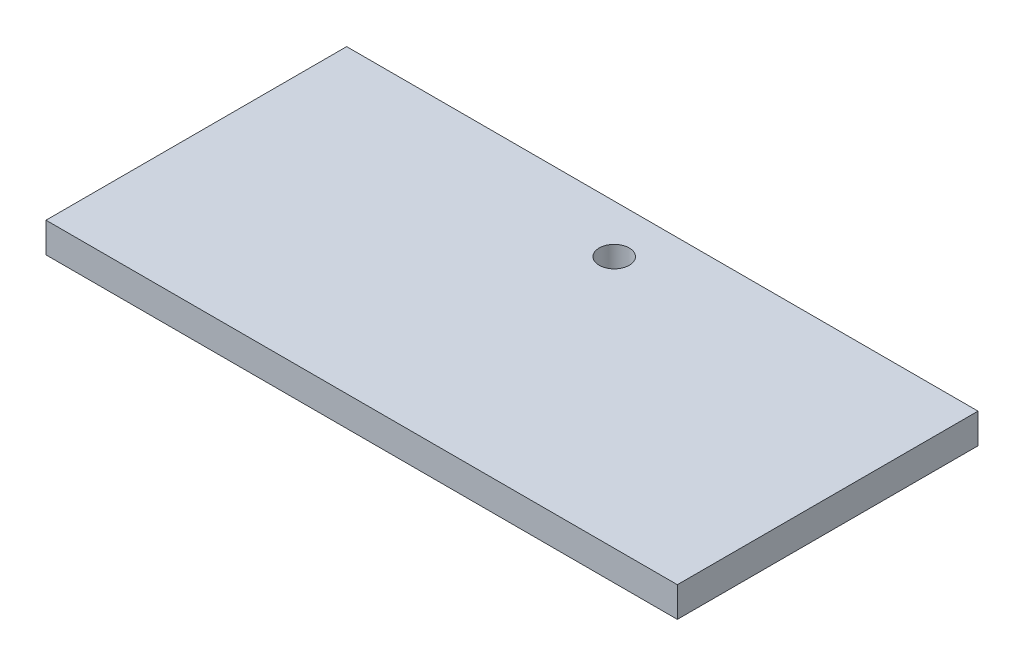
SolidWorks part; units mm, degrees
material "Pino"
ref_plane "Alzado" through (0, 0, 0) normal (0, 0, 1) x (1, 0, 0)
ref_plane "Planta" through (0, 0, 0) normal (0, 1, 0) x (1, 0, 0)
ref_plane "Vista lateral" through (0, 0, 0) normal (1, 0, 0) x (0, 0, -1)
sketch "Croquis2" plane through (0, 0, 0) normal (0, 1, 0) x (1, 0, 0)
  line L1 (0, 0) -> (1050, 0)
  line L2 (0, 0) -> (0, 500)
  line L3 (0, 500) -> (1050, 500)
  line L4 (1050, 0) -> (1050, 500)
  circle A0 centre (525, 420) radius 25
  dimension "D3" = 50
  dimension "D5" = 80
  dimension "D1" = 1050
  dimension "D2" = 500
  dimension "D4" = 525
extrude "Saliente-Extruir1" add sketch "Croquis2" along normal blind 50
